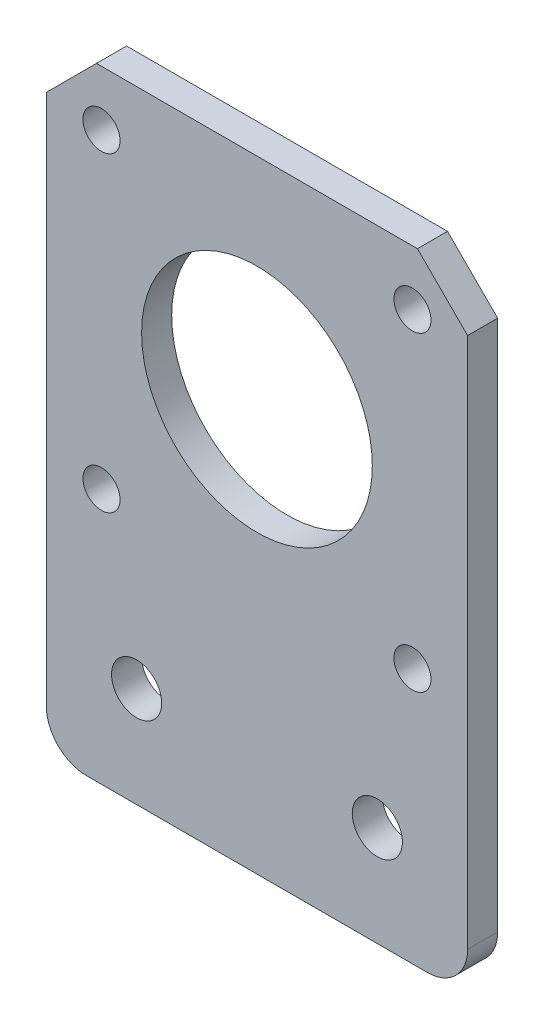
SolidWorks part; units mm, degrees
ref_plane "前基準面" through (0, 0, 0) normal (0, 0, 1) x (1, 0, 0)
ref_plane "上基準面" through (0, 0, 0) normal (0, 1, 0) x (1, 0, 0)
ref_plane "右基準面" through (0, 0, 0) normal (1, 0, 0) x (0, 0, -1)
sketch "草圖1" plane through (0, 0, 0) normal (0, 0, 1) x (1, 0, 0)
  line L0 (-21, 0) -> (21, 0) construction
  line L1 (-21, 21) -> (21, 21)
  line L2 (-21, 21) -> (-21, -21)
  line L3 (0, 21) -> (0, -41) construction
  line L4 (21, 21) -> (21, -21)
  line L6 (-21, -21) -> (-21, -41)
  line L7 (-21, -41) -> (21, -41)
  line L8 (21, -21) -> (21, -41)
  circle A0 centre (-15.5, 15.5) radius 1.8497
  circle A1 centre (15.5, 15.5) radius 1.8497
  circle A2 centre (15.5, -15.5) radius 1.8497
  circle A3 centre (-15.5, -15.5) radius 1.8497
  circle A4 centre (-12, -31) radius 2.5
  circle A5 centre (12, -31) radius 2.5
  circle A6 centre (0, 0) radius 11.5
  point P4 (0, 21)
  point P5 (-21, 0)
  dimension "D4" = 5.5
  dimension "D8" = 5
  dimension "D9" = 23
  dimension "D1" = 42
  dimension "D2" = 42
  dimension "D3" = 20
  dimension "D5" = 5.5
  dimension "D6" = 10
  dimension "D7" = 12
extrude "填料-伸長1" add sketch "草圖1" along normal blind 3
fillet "圓角1" radius 4 2 edges at (21, -41, 1.5) (-21, -41, 1.5)
chamfer "導角1" distance 5 angle 45 2 edges at (21, 21, 1.5) (-21, 21, 1.5)
sketch "草圖2" plane through (0, 0, 3) normal (0, 0, 1) x (1, 0, 0)
  line L0 (0, 21) -> (0, -41) construction
  line L1 (16, 21) -> (-16, 21) construction
  line L2 (-17, -41) -> (17, -41) construction
